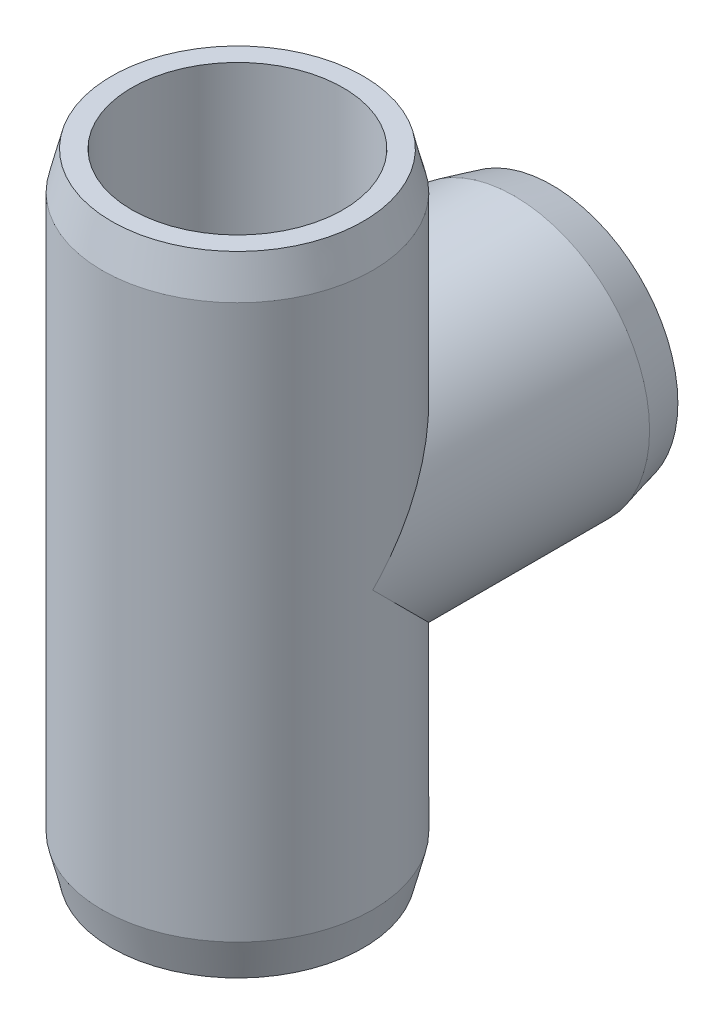
SolidWorks part; units mm, degrees
ref_plane "Front Plane" through (0, 0, 0) normal (0, 0, 1) x (1, 0, 0)
ref_plane "Top Plane" through (0, 0, 0) normal (0, 1, 0) x (1, 0, 0)
ref_plane "Right Plane" through (0, 0, 0) normal (1, 0, 0) x (0, 0, -1)
sketch "Sketch1" plane through (0, 0, 0) normal (0, 1, 0) x (1, 0, 0)
  circle A0 centre (0, 0) radius 10.668
  circle A1 centre (0, 0) radius 13.6525
  dimension "D1" = 27.305
  dimension "D2" = 21.336
extrude "Boss-Extrude1" add sketch "Sketch1" along normal blind 63.5
sketch "Sketch3" plane through (0, 0, 0) normal (0, 0, 1) x (1, 0, 0)
  line L0 (0, 0) -> (0, 63.5) construction
  circle A0 centre (0, 31.75) radius 10.668
  dimension "D2" = 21.336
  dimension "D1" = 63.5
extrude "Cut-Extrude2" cut sketch "Sketch3" against normal blind 69.85
ref_plane "Plane1" through (0, 0, -31.75) normal (0, 0, 1) x (1, 0, 0)
sketch "Sketch4" plane through (0, 0, -31.75) normal (0, 0, 1) x (1, 0, 0)
  line L0 (0, 0) -> (0, 76.2) construction
  circle A0 centre (0, 31.75) radius 13.6525
  circle A1 centre (0, 31.75) radius 10.668
  dimension "D2" = 27.305
  dimension "D3" = 21.336
  dimension "D1" = 76.2
  dimension "D4" = 31.75
extrude "Boss-Extrude2" add sketch "Sketch4" along normal up to surface (31.75 mm away)
sketch "Sketch5" plane through (0, 0, 0) normal (1, 0, 0) x (0, 0, -1)
  line L0 (31.75, 21.082) -> (31.75, 42.418) construction
  line L1 (31.75, 21.082) -> (31.75, 42.418) construction
  line L2 (10.795, 21.082) -> (10.795, 22.352)
  line L3 (10.668, 21.082) -> (31.75, 21.082) construction
  line L4 (10.795, 22.352) -> (12.7, 22.352)
  line L5 (12.7, 22.352) -> (12.7, 21.082)
  line L6 (12.7, 21.082) -> (10.795, 21.082)
  line L7 (31.75, 31.75) -> (3.9319, 31.75) construction
  dimension "D1" = 1.27
  dimension "D2" = 19.05
  dimension "D3" = 1.905
revolve "Revolve1" add sketch "Sketch5" angle 360 about L7
sketch "Sketch6" plane through (0, 0, 0) normal (1, 0, 0) x (0, 0, -1)
  line L0 (10.668, 63.5) -> (-10.668, 63.5) construction
  line L1 (10.668, 63.5) -> (-10.668, 63.5) construction
  line L2 (10.668, 42.545) -> (9.398, 42.545)
  line L3 (9.398, 42.545) -> (9.398, 44.45)
  line L4 (9.398, 44.45) -> (10.668, 44.45)
  line L5 (10.668, 44.45) -> (10.668, 42.545)
  line L6 (0, 63.5) -> (0, 26.7174) construction
  dimension "D1" = 19.05
  dimension "D2" = 1.27
  dimension "D3" = 1.905
revolve "Revolve2" add sketch "Sketch6" angle 360 about L6
sketch "Sketch7" plane through (0, 0, 0) normal (1, 0, 0) x (0, 0, -1)
  line L0 (-10.668, 0) -> (10.668, 0) construction
  line L1 (-10.668, 0) -> (10.668, 0) construction
  line L2 (-10.668, 20.955) -> (-9.398, 20.955)
  line L3 (-10.668, 42.545) -> (-10.668, 0) construction
  line L4 (-9.398, 20.955) -> (-9.398, 19.05)
  line L5 (-9.398, 19.05) -> (-10.668, 19.05)
  line L6 (-10.668, 19.05) -> (-10.668, 20.955)
  line L7 (0, 0) -> (0, 59.3654) construction
  dimension "D1" = 19.05
  dimension "D2" = 1.905
  dimension "D3" = 1.27
revolve "Revolve3" add sketch "Sketch7" angle 360 about L7
sketch "Sketch8" plane through (0, 0, 0) normal (0, 0, 1) x (1, 0, 0)
  line L0 (-13.6525, 0) -> (13.6525, 0) construction
  line L1 (-13.6525, 0) -> (13.6525, 0) construction
  line L2 (13.6525, 0) -> (13.6525, 3.81)
  line L3 (13.6525, 0) -> (13.6525, 31.75) construction
  line L4 (13.6525, 0) -> (12.7, 0)
  line L5 (12.7, 0) -> (13.6525, 3.81)
  line L6 (0, 0) -> (0, 18.431) construction
  dimension "D1" = 3.81
  dimension "D2" = 0.9525
revolve "Cut-Revolve1" cut sketch "Sketch8" angle 360 about L6
ref_plane "Plane2" through (0, 31.75, 0) normal (0, 1, 0) x (1, 0, 0)
mirror "Mirror1" about plane through (0, 31.75, 0) normal (0, 1, 0) of "Cut-Revolve1"
sketch "Sketch9" plane through (0, 0, 0) normal (1, 0, 0) x (0, 0, -1)
  line L0 (31.75, 18.0975) -> (27.94, 18.0975)
  line L1 (13.6525, 18.0975) -> (31.75, 18.0975) construction
  line L2 (31.75, 18.0975) -> (31.75, 19.05)
  line L3 (31.75, 19.05) -> (27.94, 18.0975)
  line L4 (31.75, 18.0975) -> (31.75, 45.4025) construction
  line L5 (31.75, 18.0975) -> (31.75, 45.4025) construction
  line L6 (31.75, 31.75) -> (24.5943, 31.75) construction
  dimension "D1" = 3.81
  dimension "D2" = 0.9525
revolve "Cut-Revolve2" cut sketch "Sketch9" angle 360 about L6
